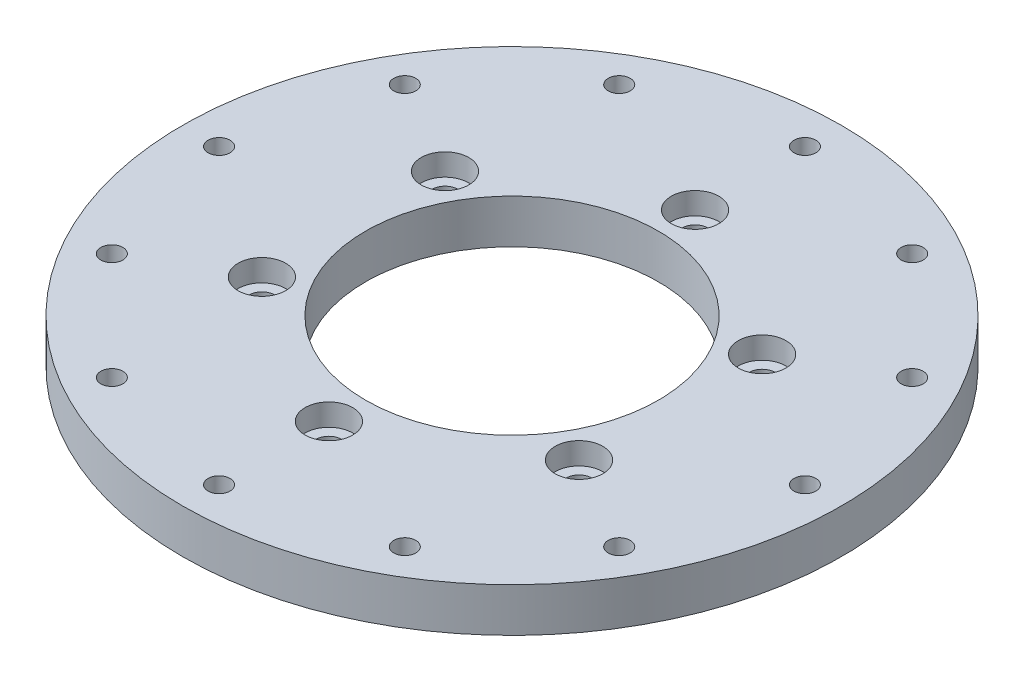
SolidWorks part; units mm, degrees
ref_plane "Front Plane" through (0, 0, 0) normal (0, 0, 1) x (1, 0, 0)
ref_plane "Top Plane" through (0, 0, 0) normal (0, 1, 0) x (1, 0, 0)
ref_plane "Right Plane" through (0, 0, 0) normal (1, 0, 0) x (0, 0, -1)
sketch "Sketch1" plane through (0, 0, 0) normal (0, 1, 0) x (1, 0, 0)
  circle A0 centre (0, 0) radius 45
  dimension "D1" = 90
extrude "Boss-Extrude1" add sketch "Sketch1" along normal blind 6
sketch "Sketch3" plane through (0, 6, 0) normal (0, 1, 0) x (1, 0, 0)
  line L0 (0, 0) -> (0, -25) construction
  circle A0 centre (0, 0) radius 25 construction
  circle A1 centre (0, -25) radius 1.75
  circle A2 centre (-21.6506, -12.5) radius 1.75
  circle A3 centre (-21.6506, 12.5) radius 1.75
  circle A4 centre (0, 25) radius 1.75
  circle A5 centre (21.6506, 12.5) radius 1.75
  circle A6 centre (21.6506, -12.5) radius 1.75
  point P17 (0, 0)
  dimension "D1" = 50
  dimension "D2" = 3.5
  dimension "D3" = 6
extrude "Cut-Extrude1" cut sketch "Sketch3" against normal through all
sketch "Sketch4" plane through (0, 6, 0) normal (0, 1, 0) x (1, 0, 0)
  circle A0 centre (0, -25) radius 3.25
  circle A1 centre (-21.6506, -12.5) radius 3.25
  circle A2 centre (-21.6506, 12.5) radius 3.25
  circle A3 centre (0, 25) radius 3.25
  circle A4 centre (21.6506, 12.5) radius 3.25
  circle A5 centre (21.6506, -12.5) radius 3.25
  point P15 (0, 0)
  dimension "D1" = 6.5
  dimension "D2" = 6
extrude "Cut-Extrude2" cut sketch "Sketch4" against normal blind 3
sketch "Sketch5" plane through (0, 6, 0) normal (0, 1, 0) x (1, 0, 0)
  line L0 (0, 0) -> (0, -45) construction
  circle A0 centre (0, 0) radius 40 construction
  circle A1 centre (0, 0) radius 45 construction
  circle A2 centre (0, -40) radius 1.5
  circle A3 centre (-20, -34.641) radius 1.5
  circle A4 centre (-34.641, -20) radius 1.5
  circle A5 centre (-40, 0) radius 1.5
  circle A6 centre (-34.641, 20) radius 1.5
  circle A7 centre (-20, 34.641) radius 1.5
  circle A8 centre (0, 40) radius 1.5
  circle A9 centre (20, 34.641) radius 1.5
  circle A10 centre (34.641, 20) radius 1.5
  circle A11 centre (40, 0) radius 1.5
  circle A12 centre (34.641, -20) radius 1.5
  circle A13 centre (20, -34.641) radius 1.5
  point P33 (0, 0)
  dimension "D1" = 80
  dimension "D2" = 3
  dimension "D3" = 12
extrude "Cut-Extrude3" cut sketch "Sketch5" against normal through all
sketch "Sketch6" plane through (0, 0, 0) normal (0, -1, 0) x (1, 0, 0)
  line L0 (0, 0) -> (0, -45) construction
  line L1 (-18.2679, -37.641) -> (-16.5359, -34.641)
  line L2 (0, -36.5359) -> (-3, -38.2679)
  line L3 (-3, -38.2679) -> (-3, -41.7321)
  line L4 (-3, -41.7321) -> (0, -43.4641)
  line L5 (0, -43.4641) -> (3, -41.7321)
  line L6 (3, -41.7321) -> (3, -38.2679)
  line L7 (3, -38.2679) -> (0, -36.5359)
  line L8 (-16.5359, -34.641) -> (-18.2679, -31.641)
  line L9 (-18.2679, -31.641) -> (-21.7321, -31.641)
  line L10 (-21.7321, -31.641) -> (-23.4641, -34.641)
  line L11 (-23.4641, -34.641) -> (-21.7321, -37.641)
  line L12 (-21.7321, -37.641) -> (-18.2679, -37.641)
  line L13 (-34.641, -23.4641) -> (-31.641, -21.7321)
  line L14 (-31.641, -21.7321) -> (-31.641, -18.2679)
  line L15 (-31.641, -18.2679) -> (-34.641, -16.5359)
  line L16 (-34.641, -16.5359) -> (-37.641, -18.2679)
  line L17 (-37.641, -18.2679) -> (-37.641, -21.7321)
  line L18 (-37.641, -21.7321) -> (-34.641, -23.4641)
  line L19 (-41.7321, -3) -> (-38.2679, -3)
  line L20 (-38.2679, -3) -> (-36.5359, 0)
  line L21 (-36.5359, 0) -> (-38.2679, 3)
  line L22 (-38.2679, 3) -> (-41.7321, 3)
  line L23 (-41.7321, 3) -> (-43.4641, 0)
  line L24 (-43.4641, 0) -> (-41.7321, -3)
  line L25 (-37.641, 18.2679) -> (-34.641, 16.5359)
  line L26 (-34.641, 16.5359) -> (-31.641, 18.2679)
  line L27 (-31.641, 18.2679) -> (-31.641, 21.7321)
  line L28 (-31.641, 21.7321) -> (-34.641, 23.4641)
  line L29 (-34.641, 23.4641) -> (-37.641, 21.7321)
  line L30 (-37.641, 21.7321) -> (-37.641, 18.2679)
  line L31 (-23.4641, 34.641) -> (-21.7321, 31.641)
  line L32 (-21.7321, 31.641) -> (-18.2679, 31.641)
  line L33 (-18.2679, 31.641) -> (-16.5359, 34.641)
  line L34 (-16.5359, 34.641) -> (-18.2679, 37.641)
  line L35 (-18.2679, 37.641) -> (-21.7321, 37.641)
  line L36 (-21.7321, 37.641) -> (-23.4641, 34.641)
  line L37 (-3, 41.7321) -> (-3, 38.2679)
  line L38 (-3, 38.2679) -> (0, 36.5359)
  line L39 (0, 36.5359) -> (3, 38.2679)
  line L40 (3, 38.2679) -> (3, 41.7321)
  line L41 (3, 41.7321) -> (0, 43.4641)
  line L42 (0, 43.4641) -> (-3, 41.7321)
  line L43 (18.2679, 37.641) -> (16.5359, 34.641)
  line L44 (16.5359, 34.641) -> (18.2679, 31.641)
  line L45 (18.2679, 31.641) -> (21.7321, 31.641)
  line L46 (21.7321, 31.641) -> (23.4641, 34.641)
  line L47 (23.4641, 34.641) -> (21.7321, 37.641)
  line L48 (21.7321, 37.641) -> (18.2679, 37.641)
  line L49 (34.641, 23.4641) -> (31.641, 21.7321)
  line L50 (31.641, 21.7321) -> (31.641, 18.2679)
  line L51 (31.641, 18.2679) -> (34.641, 16.5359)
  line L52 (34.641, 16.5359) -> (37.641, 18.2679)
  line L53 (37.641, 18.2679) -> (37.641, 21.7321)
  line L54 (37.641, 21.7321) -> (34.641, 23.4641)
  line L55 (41.7321, 3) -> (38.2679, 3)
  line L56 (38.2679, 3) -> (36.5359, 0)
  line L57 (36.5359, 0) -> (38.2679, -3)
  line L58 (38.2679, -3) -> (41.7321, -3)
  line L59 (41.7321, -3) -> (43.4641, 0)
  line L60 (43.4641, 0) -> (41.7321, 3)
  line L61 (37.641, -18.2679) -> (34.641, -16.5359)
  line L62 (34.641, -16.5359) -> (31.641, -18.2679)
  line L63 (31.641, -18.2679) -> (31.641, -21.7321)
  line L64 (31.641, -21.7321) -> (34.641, -23.4641)
  line L65 (34.641, -23.4641) -> (37.641, -21.7321)
  line L66 (37.641, -21.7321) -> (37.641, -18.2679)
  line L67 (23.4641, -34.641) -> (21.7321, -31.641)
  line L68 (21.7321, -31.641) -> (18.2679, -31.641)
  line L69 (18.2679, -31.641) -> (16.5359, -34.641)
  line L70 (16.5359, -34.641) -> (18.2679, -37.641)
  line L71 (18.2679, -37.641) -> (21.7321, -37.641)
  line L72 (21.7321, -37.641) -> (23.4641, -34.641)
  circle A0 centre (0, 0) radius 45 construction
  circle A1 centre (0, -40) radius 3 construction
  point P83 (0, 0)
  dimension "D1" = 6
  dimension "D2" = 12
extrude "Cut-Extrude4" cut sketch "Sketch6" against normal blind 3
sketch "Sketch9" plane through (0, 6, 0) normal (0, 1, 0) x (1, 0, 0)
  circle A0 centre (0, 0) radius 20
  dimension "D1" = 40
extrude "Cut-Extrude5" cut sketch "Sketch9" against normal through all
